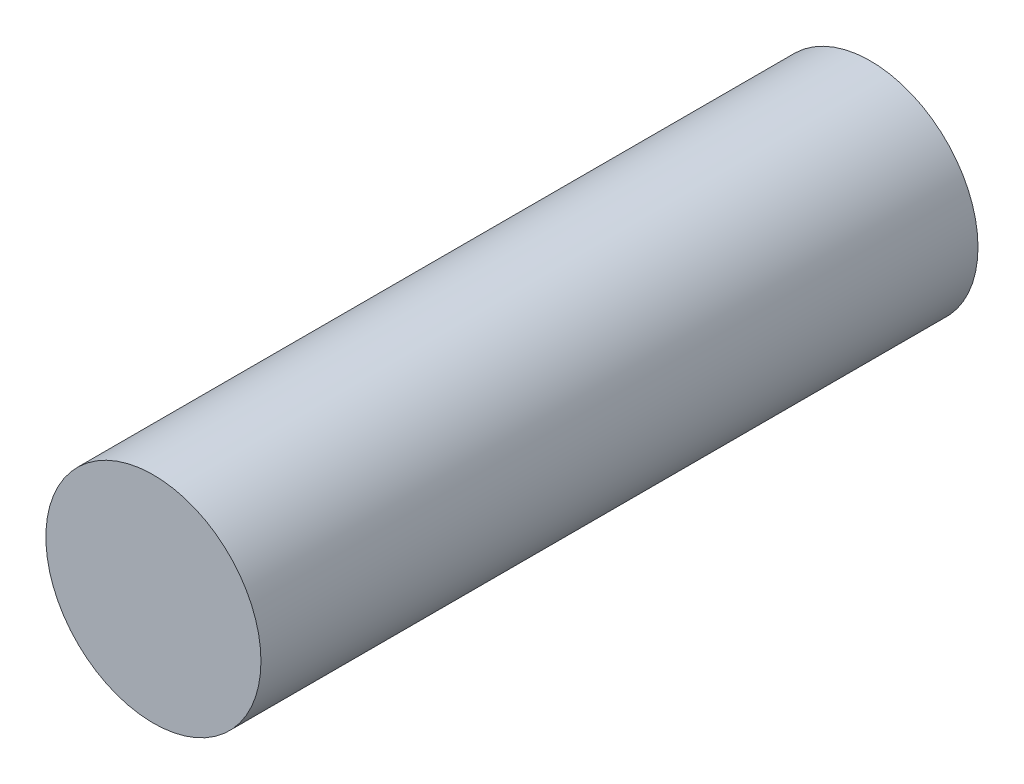
SolidWorks part; units mm, degrees
ref_plane "Front Plane" through (0, 0, 0) normal (0, 0, 1) x (1, 0, 0)
ref_plane "Top Plane" through (0, 0, 0) normal (0, 1, 0) x (1, 0, 0)
ref_plane "Right Plane" through (0, 0, 0) normal (1, 0, 0) x (0, 0, -1)
other "Configuration Table"
sketch "Sketch1" plane through (0, 0, 0) normal (0, 0, 1) x (1, 0, 0)
  circle A0 centre (0, 140) radius 15
extrude "KAPYAG_samandira_D30" add sketch "Sketch1" against normal blind 100 from offset 300 separate body
